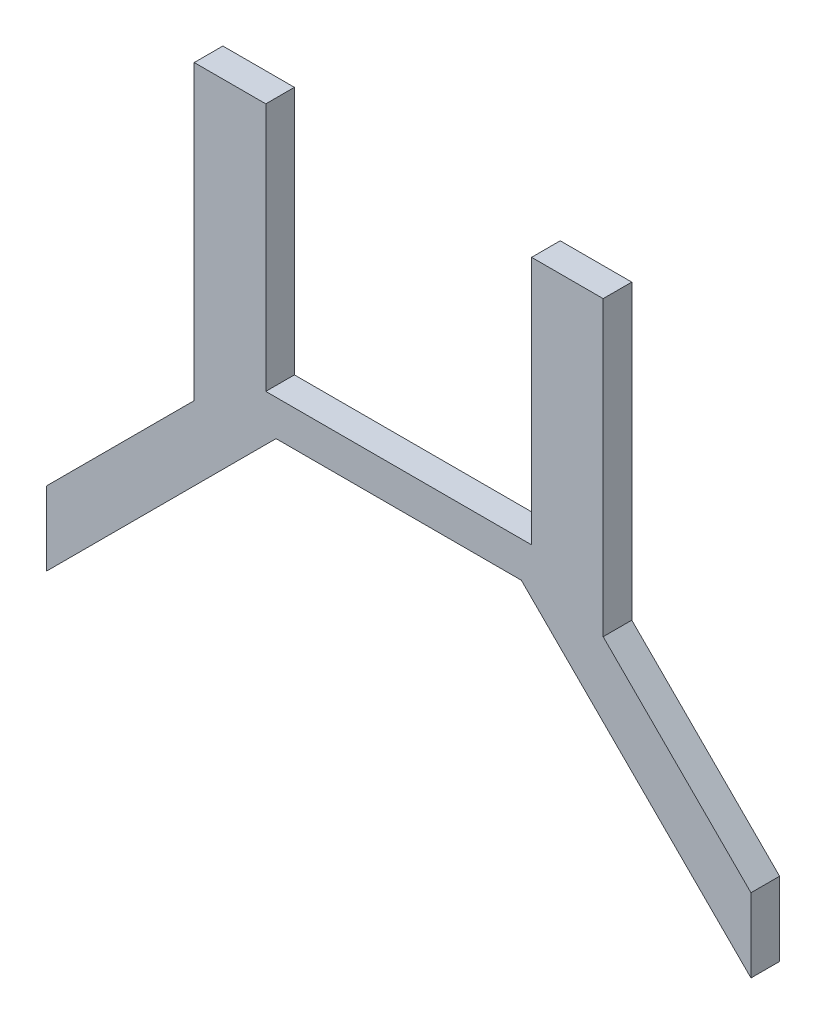
SolidWorks part; units mm, degrees
ref_plane "Front Plane" through (0, 0, 0) normal (0, 0, 1) x (1, 0, 0)
ref_plane "Top Plane" through (0, 0, 0) normal (0, 1, 0) x (1, 0, 0)
ref_plane "Right Plane" through (0, 0, 0) normal (1, 0, 0) x (0, 0, -1)
ref_plane "Plan1" through (0, 0, 0) normal (0, 0, -1) x (-1, 0, 0)
sketch "Esquisse1" plane through (0, 0, 0) normal (0, 0, -1) x (-1, 0, 0)
  line L0 (43.9182, 28.0081) -> (2.5994, -13.3107)
  line L1 (2.5994, -13.3107) -> (2.5994, -33.9499)
  line L2 (2.5994, -33.9499) -> (66.7865, 30.2372)
  line L3 (66.7865, 30.2372) -> (135.3499, 30.2372)
  line L4 (135.3499, 30.2372) -> (199.537, -33.9499)
  line L5 (199.537, -33.9499) -> (199.537, -13.3107)
  line L6 (199.537, -13.3107) -> (158.2182, 28.0081)
  line L7 (158.2182, 28.0081) -> (158.2182, 109.8482)
  line L8 (158.2182, 109.8482) -> (138.2182, 109.8482)
  line L9 (138.2182, 109.8482) -> (138.2182, 40.2372)
  line L10 (138.2182, 40.2372) -> (63.9182, 40.2372)
  line L11 (63.9182, 40.2372) -> (63.9182, 109.8482)
  line L12 (63.9182, 109.8482) -> (43.9182, 109.8482)
  line L13 (43.9182, 109.8482) -> (43.9182, 28.0081)
  line L14 (101.0682, 40.2372) -> (101.0682, 4.6046) construction
  dimension "D1" = 20
  dimension "D2" = 20
  dimension "D3" = 74.3
extrude "Boss.-Extru.1" add sketch "Esquisse1" against normal blind 8
